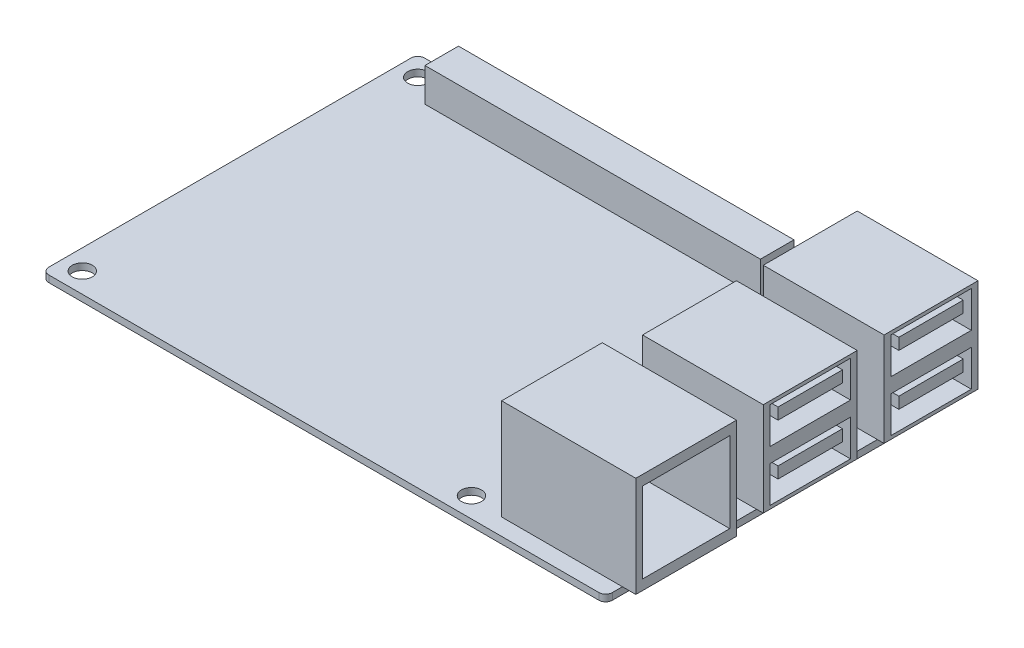
SolidWorks part; units mm, degrees
ref_plane "Спереди" through (0, 0, 0) normal (0, 0, 1) x (1, 0, 0)
ref_plane "Сверху" through (0, 0, 0) normal (0, 1, 0) x (1, 0, 0)
ref_plane "Справа" through (0, 0, 0) normal (1, 0, 0) x (0, 0, -1)
sketch "Эскиз1" plane through (0, 0, 0) normal (0, 1, 0) x (1, 0, 0)
  line L1 (1, 0) -> (83, 0)
  line L2 (0, 1) -> (0, 55)
  line L3 (1, 56) -> (83, 56)
  line L4 (84, 1) -> (84, 55)
  arc A0 (84, 55) -> (83, 56) centre (83, 55) ccw
  arc A1 (83, 0) -> (84, 1) centre (83, 1) ccw
  arc A2 (1, 0) -> (0, 1) centre (1, 1) cw
  arc A3 (1, 56) -> (0, 55) centre (1, 55) ccw
  circle A4 centre (3, 53) radius 1.5
  circle A5 centre (61, 53) radius 1.5
  circle A6 centre (61, 3) radius 1.5
  circle A7 centre (3, 3) radius 1.5
  point P7 (84, 56)
  point P12 (0, 0)
  point P15 (0, 56)
  dimension "D3" = 1
  dimension "D4" = 3
  dimension "D1" = 56
  dimension "D2" = 84
  dimension "D5" = 3
  dimension "D6" = 3
  dimension "D7" = 3
  dimension "D8" = 23
  dimension "D9" = 3
  dimension "D10" = 23
  dimension "D11" = 3
extrude "Бобышка-Вытянуть1" add sketch "Эскиз1" along normal blind 1
sketch "Эскиз2" plane through (0, 1, 0) normal (0, 1, 0) x (1, 0, 0)
  line L0 (0, 55) -> (0, 1) construction
  line L1 (7, 55.0676) -> (57, 55.0676)
  line L2 (7, 55.0676) -> (7, 50.0676)
  line L3 (7, 50.0676) -> (57, 50.0676)
  line L4 (57, 55.0676) -> (57, 50.0676)
  dimension "D1" = 50
  dimension "D2" = 5
  dimension "D3" = 7
sketch "Эскиз3" plane through (0, 1, 0) normal (0, 1, 0) x (1, 0, 0)
  line L0 (84, 1) -> (84, 55) construction
  line L1 (68, 35.5) -> (86, 35.5)
  line L2 (68, 35.5) -> (68, 21.5)
  line L3 (68, 21.5) -> (86, 21.5)
  line L4 (86, 35.5) -> (86, 21.5)
  line L5 (66, 17.5) -> (86, 17.5)
  line L6 (66, 17.5) -> (66, 2.5)
  line L7 (66, 2.5) -> (86, 2.5)
  line L8 (86, 17.5) -> (86, 2.5)
  line L9 (1, 0) -> (83, 0) construction
  line L10 (68, 53.5) -> (86, 53.5)
  line L11 (86, 53.5) -> (86, 39.5)
  line L12 (68, 39.5) -> (86, 39.5)
  line L13 (68, 53.5) -> (68, 39.5)
  line L14 (83, 56) -> (1, 56) construction
  dimension "D1" = 20
  dimension "D2" = 15
  dimension "D3" = 18
  dimension "D4" = 14
  dimension "D5" = 2
  dimension "D6" = 2
  dimension "D7" = 2.5
  dimension "D8" = 4
  dimension "D9" = 18
  dimension "D10" = 14
  dimension "D11" = 2
  dimension "D12" = 2.5
  dimension "D13" = 51
extrude "Бобышка-Вытянуть2" add sketch "Эскиз3" along normal blind 15
sketch "Эскиз4" plane through (86, 0, 0) normal (1, 0, 0) x (0, 0, -1)
  line L0 (39.5, 16) -> (53.5, 16) construction
  line L1 (40.5, 15.5) -> (52.5, 15.5)
  line L2 (40.5, 15.5) -> (40.5, 10.1)
  line L3 (40.5, 2.5) -> (52.5, 2.5)
  line L4 (52.5, 15.5) -> (52.5, 10.1)
  line L5 (39.5, 1) -> (53.5, 1) construction
  line L6 (21.5, 16) -> (21.5, 1) construction
  line L8 (40.5, 7.9) -> (40.5, 2.5)
  line L9 (40.5, 10.1) -> (52.5, 10.1)
  line L10 (52.5, 7.9) -> (52.5, 2.5)
  line L11 (40.5, 7.9) -> (52.5, 7.9)
  line L12 (21.5, 16) -> (35.5, 16) construction
  line L13 (41.7, 14.6) -> (51.3, 14.6)
  line L14 (41.7, 14.6) -> (41.7, 12.9)
  line L15 (41.7, 12.9) -> (51.3, 12.9)
  line L16 (51.3, 14.6) -> (51.3, 12.9)
  line L17 (41.7, 7) -> (51.3, 7)
  line L18 (41.7, 7) -> (41.7, 5.3)
  line L19 (41.7, 5.3) -> (51.3, 5.3)
  line L20 (51.3, 7) -> (51.3, 5.3)
  line L21 (35.05, 16.7567) -> (35.05, 8.9185) construction
  line L22 (35.5, 16) -> (35.5, 1) construction
  line L23 (22.5, 7.9) -> (34.5, 7.9)
  line L24 (23.7, 14.6) -> (33.3, 14.6)
  line L25 (23.7, 7) -> (33.3, 7)
  line L26 (22.5, 15.5) -> (22.5, 10.1)
  line L27 (23.7, 7) -> (23.7, 5.3)
  line L28 (23.7, 12.9) -> (33.3, 12.9)
  line L29 (22.5, 7.9) -> (22.5, 2.5)
  line L30 (22.5, 2.5) -> (34.5, 2.5)
  line L31 (23.7, 14.6) -> (23.7, 12.9)
  line L32 (34.5, 7.9) -> (34.5, 2.5)
  line L33 (33.3, 14.6) -> (33.3, 12.9)
  line L34 (34.5, 15.5) -> (34.5, 10.1)
  line L35 (33.3, 7) -> (33.3, 5.3)
  line L36 (22.5, 10.1) -> (34.5, 10.1)
  line L37 (23.7, 5.3) -> (33.3, 5.3)
  line L38 (22.5, 15.5) -> (34.5, 15.5)
  line L39 (21.5, 1) -> (35.5, 1) construction
  line L40 (53.5, 16) -> (53.5, 1) construction
  dimension "D1" = 0.5
  dimension "D2" = 1.5
  dimension "D3" = 1.7
  dimension "D4" = 0.9
  dimension "D5" = 2.2
  dimension "D6" = 1.5
  dimension "D7" = 0.9
  dimension "D8" = 1.2
  dimension "D9" = 1.2
  dimension "D10" = 1
  dimension "D11" = 0.9
  dimension "D12" = 1.7
  dimension "D13" = 1.2
  dimension "D14" = 1.2
  dimension "D15" = 1
  dimension "D16" = 2.2
  dimension "D17" = 0.9
  dimension "D18" = 0.5
  dimension "D19" = 13
  dimension "D20" = 1
  dimension "D21" = 1
  dimension "D22" = 1.2
  dimension "D23" = 1.2
  dimension "D24" = 1
extrude "Вырез-Вытянуть1" cut sketch "Эскиз4" against normal blind 14
sketch "Эскиз5" plane through (86, 0, 0) normal (1, 0, 0) x (0, 0, -1)
  line L0 (2.5, 16) -> (17.5, 16) construction
  line L1 (3.5, 14.5) -> (16.5, 14.5)
  line L2 (3.5, 14.5) -> (3.5, 2.5)
  line L3 (3.5, 2.5) -> (16.5, 2.5)
  line L4 (16.5, 14.5) -> (16.5, 2.5)
  line L5 (2.5, 1) -> (17.5, 1) construction
  line L6 (2.5, 16) -> (2.5, 1) construction
  line L7 (17.5, 16) -> (17.5, 1) construction
  dimension "D1" = 1.5
  dimension "D2" = 1.5
  dimension "D3" = 1
  dimension "D4" = 1
extrude "Вырез-Вытянуть2" cut sketch "Эскиз5" against normal blind 14
extrude "Бобышка-Вытянуть3" add sketch "Эскиз2" along normal blind 5
sketch "Эскиз7" plane through (86, 0, 0) normal (1, 0, 0) x (0, 0, -1)
  line L0 (21.5, 16) -> (21.5, 1) construction
  line L1 (21.5, 2) -> (35.5, 2)
  line L2 (21.5, 2) -> (21.5, 1)
  line L3 (21.5, 1) -> (35.5, 1)
  line L4 (35.5, 2) -> (35.5, 1)
  line L5 (39.5, 16) -> (39.5, 1) construction
  line L6 (39.5, 2) -> (53.5, 2)
  line L7 (39.5, 2) -> (39.5, 1)
  line L8 (39.5, 1) -> (53.5, 1)
  line L9 (53.5, 2) -> (53.5, 1)
  dimension "D1" = 1
extrude "Вырез-Вытянуть5" cut sketch "Эскиз7" against normal blind 5
